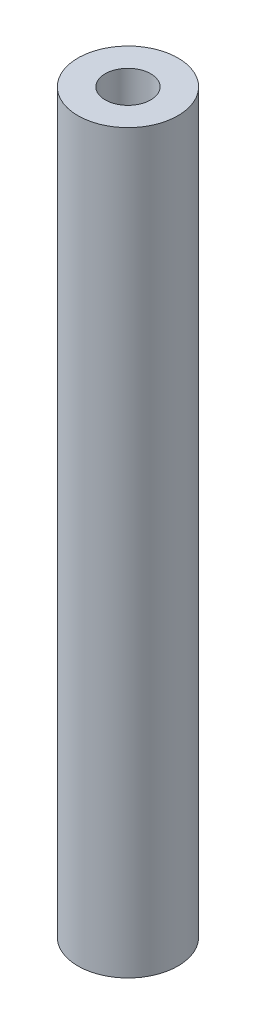
SolidWorks part; units mm, degrees
material "1023 Carbon Steel Sheet (SS)"
ref_plane "Front Plane" through (0, 0, 0) normal (0, 0, 1) x (1, 0, 0)
ref_plane "Top Plane" through (0, 0, 0) normal (0, 1, 0) x (1, 0, 0)
ref_plane "Right Plane" through (0, 0, 0) normal (1, 0, 0) x (0, 0, -1)
sketch "Sketch1" plane through (0, 0, 0) normal (0, 1, 0) x (1, 0, 0)
  circle A0 centre (0, 0) radius 2.5
  circle A1 centre (0, 0) radius 5.5
  dimension "D1" = 3
  dimension "D2" = 5
extrude "Boss-Extrude1" add sketch "Sketch1" along normal blind 81
